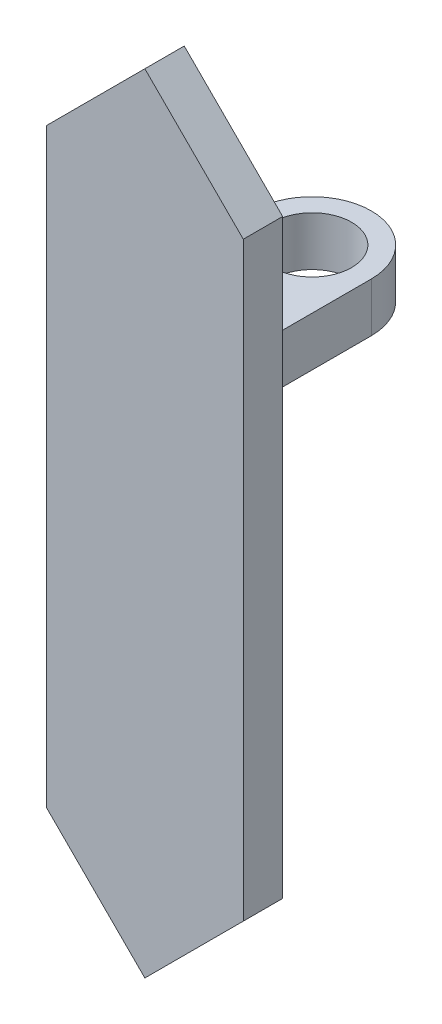
SolidWorks part; units mm, degrees
ref_plane "前视基准面" through (0, 0, 0) normal (0, 0, 1) x (1, 0, 0)
ref_plane "上视基准面" through (0, 0, 0) normal (0, 1, 0) x (1, 0, 0)
ref_plane "右视基准面" through (0, 0, 0) normal (1, 0, 0) x (0, 0, -1)
sketch "草图1" plane through (0, 0, 0) normal (0, 0, 1) x (1, 0, 0)
  line L2 (0.1473, 10) -> (0.1473, 70)
  line L4 (20.1473, 10) -> (20.1473, 70)
  line L5 (0.1473, 70) -> (10.1473, 80)
  line L6 (10.1473, 80) -> (20.1473, 70)
  line L8 (10.1473, 0) -> (20.1473, 10)
  line L9 (0.1473, 10) -> (10.1473, 0)
extrude "凸台-拉伸1" add sketch "草图1" along normal blind 4 contours L2 L9 L8 L4 L6 L5
sketch "草图2" plane through (0, 0, 0) normal (0, 0, -1) x (-1, 0, 0)
  line L0 (-10.1473, 56) -> (-10.1473, 80)
  line L5 (-16.1473, 56) -> (-4.1473, 56)
  line L6 (-16.1473, 56) -> (-16.1473, 51)
  line L7 (-16.1473, 51) -> (-4.1473, 51)
  line L8 (-4.1473, 56) -> (-4.1473, 51)
  line L9 (-16.1473, 56) -> (-4.1473, 51) construction
  line L10 (-16.1473, 51) -> (-4.1473, 56) construction
  point P8 (-10.1473, 53.5)
  dimension "D1" = 24
extrude "凸台-拉伸2" add sketch "草图2" along normal blind 20 contours L8 L5 L6 L7
sketch "草图6" plane through (0, 51, 0) normal (0, -1, 0) x (1, 0, 0)
  line L0 (10.1473, -13) -> (10.1473, 0)
  line L1 (16.1473, 0) -> (4.1473, 0) construction
  circle A0 centre (10.1473, -13) radius 6
  circle A1 centre (10.1473, -13) radius 4
  dimension "D2" = 12
  dimension "D1" = 13
extrude "切除-拉伸5" cut sketch "草图6" against normal blind 21
